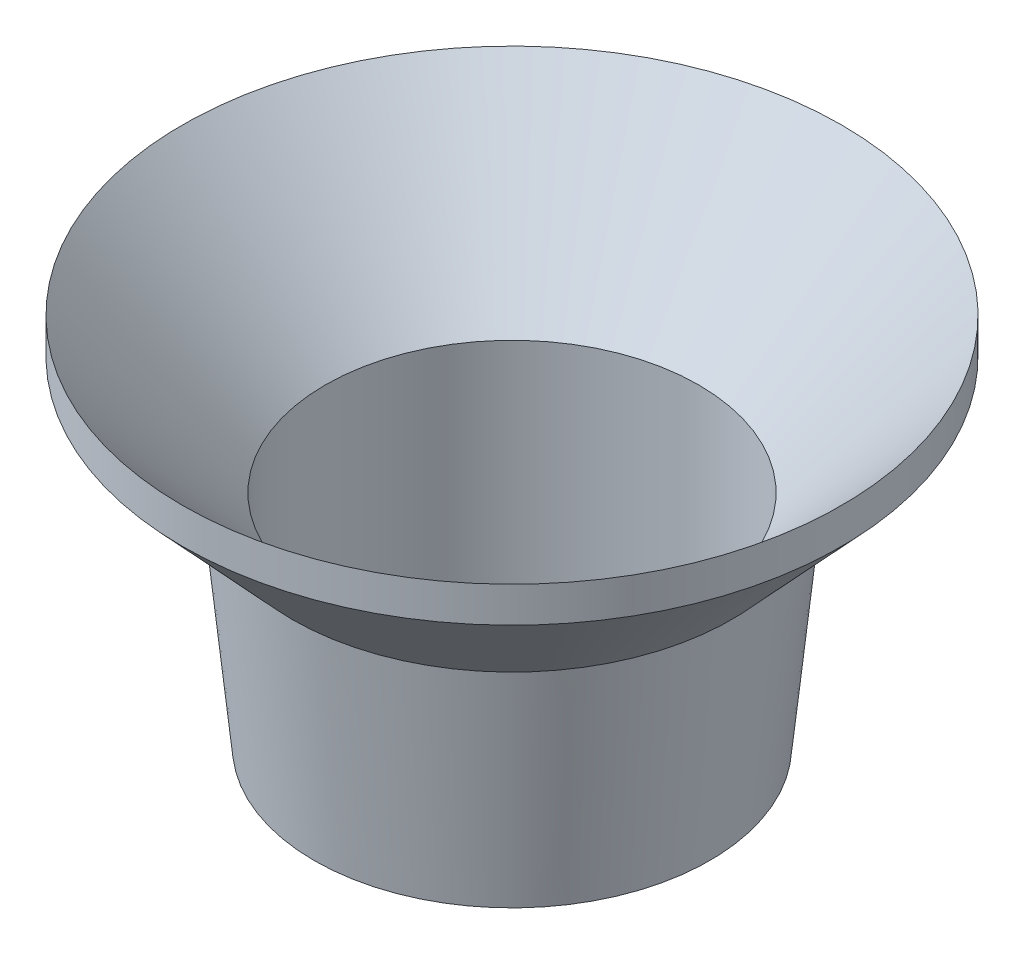
SolidWorks part; units mm, degrees
ref_plane "Front Plane" through (0, 0, 0) normal (0, 0, 1) x (1, 0, 0)
ref_plane "Top Plane" through (0, 0, 0) normal (0, 1, 0) x (1, 0, 0)
ref_plane "Right Plane" through (0, 0, 0) normal (1, 0, 0) x (0, 0, -1)
sketch "Sketch1" plane through (0, 0, 0) normal (1, 0, 0) x (0, 0, -1)
  line L0 (0, 20.7759) -> (0, -17.069) construction
  line L1 (-15, 10.3846) -> (-10, 5)
  line L2 (-10, 5) -> (-10, -5) construction
  line L3 (-15, 12) -> (-8.5, 5)
  line L4 (-8.5, 5) -> (-8.5, -5)
  line L5 (-8.5, -5) -> (-9.0019, -5)
  line L6 (-15, 12) -> (-15, 10.3846)
  line L7 (-9.0019, -5) -> (-10, 5)
  line L8 (-9.0019, -5) -> (-10, -5) construction
  point P13 (-8.5, 0)
  dimension "D1" = 7
  dimension "D2" = 30
  dimension "D3" = 5.7
  dimension "D4" = 10
  dimension "D5" = 10
revolve "Revolve1" add sketch "Sketch1" angle 360 about L0
